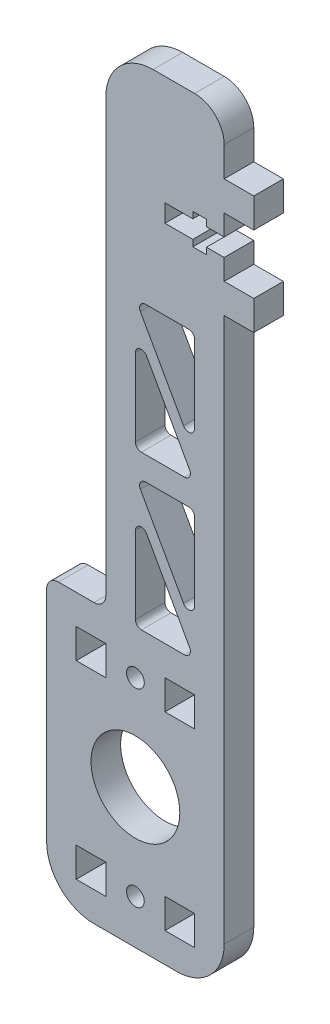
SolidWorks part; units mm, degrees
ref_plane "Plan de face" through (0, 0, 0) normal (0, 0, 1) x (1, 0, 0)
ref_plane "Plan de dessus" through (0, 0, 0) normal (0, 1, 0) x (1, 0, 0)
ref_plane "Plan de droite" through (0, 0, 0) normal (1, 0, 0) x (0, 0, -1)
sketch "Esquisse1" plane through (0, 0, 0) normal (0, 0, 1) x (1, 0, 0)
  line L0 (0, 0) -> (0, -92)
  line L1 (-8, -100) -> (-22, -100)
  line L2 (-28, -53) -> (-22, -53)
  line L3 (-20, -51) -> (-20, 22)
  line L4 (-5, -90) -> (-10, -90)
  line L5 (-5, -90) -> (-5, -95)
  line L6 (-5, -95) -> (-10, -95)
  line L7 (-10, -90) -> (-10, -95)
  line L8 (-20, -90) -> (-25, -90)
  line L9 (-20, -90) -> (-20, -95)
  line L10 (-20, -95) -> (-25, -95)
  line L11 (-25, -90) -> (-25, -95)
  line L12 (-20, -58) -> (-25, -58)
  line L13 (-20, -58) -> (-20, -63)
  line L14 (-20, -63) -> (-25, -63)
  line L15 (-25, -58) -> (-25, -63)
  line L16 (-5, -58) -> (-10, -58)
  line L17 (-5, -58) -> (-5, -63)
  line L18 (-30, -92) -> (-30, -55)
  line L19 (0, 25) -> (0, 20)
  line L20 (0, 20) -> (5, 20)
  line L21 (5, 20) -> (5, 15)
  line L22 (-5, -63) -> (-10, -63)
  line L23 (-3, 11.5) -> (-3, 12.6)
  line L24 (-3, 12.6) -> (-5.3, 12.6)
  line L25 (-5.3, 12.6) -> (-5.3, 11.5)
  line L26 (-5.3, 11.5) -> (-10, 11.5)
  line L27 (-10, 11.5) -> (-10, 8.5)
  line L28 (-10, 8.5) -> (-5.3, 8.5)
  line L29 (-5.3, 8.5) -> (-5.3, 7.4)
  line L30 (-5.3, 7.4) -> (-3, 7.4)
  line L31 (-3, 7.4) -> (-3, 8.5)
  line L32 (-10, -58) -> (-10, -63)
  line L33 (5, 5) -> (5, 0)
  line L34 (5, 0) -> (0, 0)
  line L35 (-6, -5) -> (-13.2958, -5)
  line L36 (-14.1688, -6.4877) -> (-6.873, -19.5468)
  line L37 (-5, -19.0591) -> (-5, -6)
  line L38 (5, 5) -> (0, 5)
  line L39 (0, 5) -> (0, 8.5)
  line L40 (0, 8.5) -> (-3, 8.5)
  line L41 (5, 15) -> (0, 15)
  line L42 (0, 15) -> (0, 11.5)
  line L43 (0, 11.5) -> (-3, 11.5)
  line L44 (-13.127, -12.4532) -> (-5.8312, -25.5123)
  line L45 (-12, 30) -> (-5, 30)
  line L46 (-6.7042, -27) -> (-14, -27)
  line L47 (-15, -26) -> (-15, -12.9409)
  line L48 (-6, -31) -> (-13.2958, -31)
  line L49 (-5, -45.0591) -> (-5, -32)
  line L50 (-14.1688, -32.4877) -> (-6.873, -45.5468)
  line L51 (-13.127, -38.4532) -> (-5.8312, -51.5123)
  line L52 (-6.7042, -53) -> (-14, -53)
  line L53 (-15, -52) -> (-15, -38.9409)
  line L54 (-10, -63) -> (-20, -90) construction
  line L55 (-10, -60.5) -> (-20, -60.5) construction
  line L56 (-10, -92.5) -> (-20, -92.5) construction
  arc A0 (-30, -92) -> (-22, -100) centre (-22, -92) ccw
  arc A1 (0, -92) -> (-8, -100) centre (-8, -92) cw
  arc A2 (-12, 30) -> (-20, 22) centre (-12, 22) ccw
  arc A3 (-30, -55) -> (-28, -53) centre (-28, -55) cw
  arc A4 (0, 25) -> (-5, 30) centre (-5, 25) ccw
  arc A5 (-22, -53) -> (-20, -51) centre (-22, -51) ccw
  arc A6 (-14, -27) -> (-15, -26) centre (-14, -26) cw
  arc A7 (-5.8312, -25.5123) -> (-6.7042, -27) centre (-6.7042, -26) cw
  arc A8 (-13.127, -12.4532) -> (-15, -12.9409) centre (-14, -12.9409) ccw
  arc A9 (-13.2958, -5) -> (-14.1688, -6.4877) centre (-13.2958, -6) ccw
  arc A10 (-6.873, -19.5468) -> (-5, -19.0591) centre (-6, -19.0591) ccw
  arc A11 (-6, -5) -> (-5, -6) centre (-6, -6) cw
  arc A12 (-6, -31) -> (-5, -32) centre (-6, -32) cw
  arc A13 (-6.873, -45.5468) -> (-5, -45.0591) centre (-6, -45.0591) ccw
  arc A14 (-13.2958, -31) -> (-14.1688, -32.4877) centre (-13.2958, -32) ccw
  arc A15 (-13.127, -38.4532) -> (-15, -38.9409) centre (-14, -38.9409) ccw
  arc A16 (-5.8312, -51.5123) -> (-6.7042, -53) centre (-6.7042, -52) cw
  arc A17 (-14, -53) -> (-15, -52) centre (-14, -52) cw
  circle A18 centre (-15, -76.5) radius 7.5
  circle A19 centre (-15, -60.5) radius 1.5
  circle A20 centre (-15, -92.5) radius 1.5
  point P2 (-7.5, -95)
  point P66 (-5, -27)
  point P69 (-15, -9.1007)
  point P72 (-15, -5)
  point P75 (-5, -22.8993)
  point P107 (-15, -92.5)
  point P108 (-15, -60.5)
  dimension "D9" = 5
  dimension "D10" = 5
  dimension "D17" = 10
  dimension "D18" = 5
  dimension "D19" = 5
  dimension "D21" = 5
  dimension "D11" = 5
  dimension "D13" = 8
  dimension "D14" = 5
  dimension "D16" = 3
  dimension "D23" = 8
  dimension "D24" = 2
  dimension "D30" = 1
  dimension "D29" = 15
  dimension "D33" = 3
  dimension "D34" = 3
  dimension "D2" = 130
  dimension "D3" = 27
  dimension "D4" = 10
  dimension "D5" = 3
  dimension "D6" = 4.7
  dimension "D7" = 1.1
  dimension "D8" = 5
  dimension "D12" = 5
  dimension "D15" = 3.5
  dimension "D20" = 5
  dimension "D22" = 20
  dimension "D25" = 5
  dimension "D26" = 5
  dimension "D27" = 2
  dimension "D28" = 5
  dimension "D32" = 5
  dimension "D31" = 2
extrude "Boss.-Extru.1" add sketch "Esquisse1" along normal blind 5
